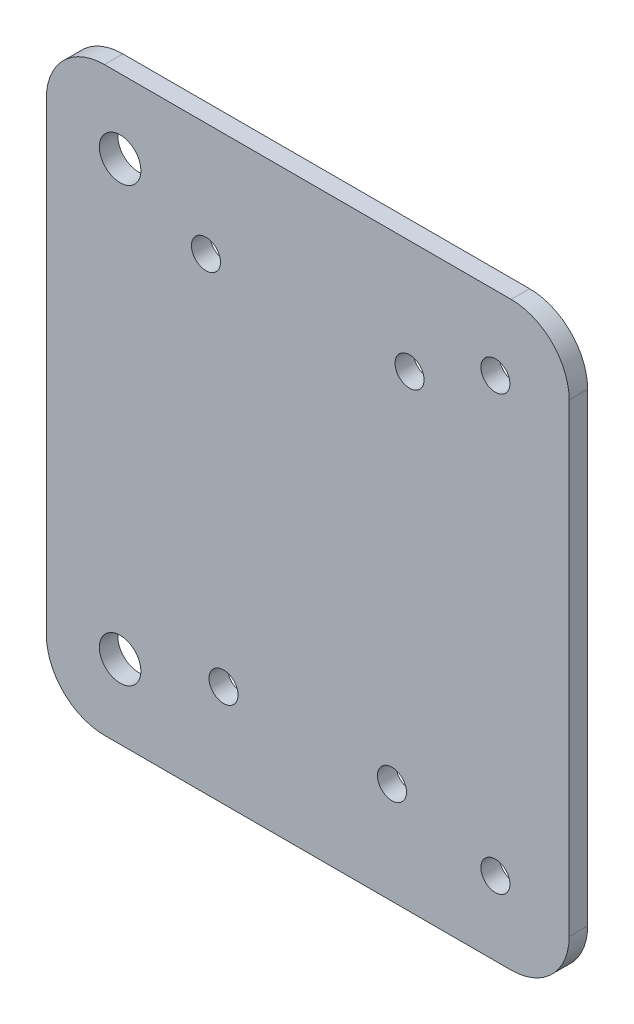
SolidWorks part; units mm, degrees
ref_plane "Front Plane" through (0, 0, 0) normal (0, 0, 1) x (1, 0, 0)
ref_plane "Top Plane" through (0, 0, 0) normal (0, 1, 0) x (1, 0, 0)
ref_plane "Right Plane" through (0, 0, 0) normal (1, 0, 0) x (0, 0, -1)
sketch "Sketch1" plane through (0, 0, 0) normal (0, 0, 1) x (1, 0, 0)
  line L1 (-45, -55) -> (45, -55)
  line L2 (-45, -55) -> (-45, 45)
  line L3 (-45, 45) -> (45, 45)
  line L4 (45, -55) -> (45, 45)
  circle A5 centre (32.3, -42.3) radius 2.5
  circle A6 centre (-32.3, -42.3) radius 3.57
  circle A9 centre (-32.3, 32.3) radius 3.57
  circle A11 centre (32.3, 32.3) radius 2.5
extrude "Boss-Extrude1" add sketch "Sketch1" against normal blind 3.18
fillet "Fillet1" radius 10 4 edges at (45, -55, -1.59) (-45, -55, -1.59) (-45, 45, -1.59) (45, 45, -1.59)
sketch "Sketch2" plane through (0, 0, 0) normal (0, 0, 1) x (1, 0, 0)
  circle A0 centre (-14.5, -37.5) radius 2.5
  circle A1 centre (14.5, -37.5) radius 2.5
  circle A2 centre (-17.5231, 25.5078) radius 2.5
  circle A3 centre (17.5231, 25.5078) radius 2.5
  dimension "D1" = 5
extrude "Cut-Extrude1" cut sketch "Sketch2" against normal blind 10
